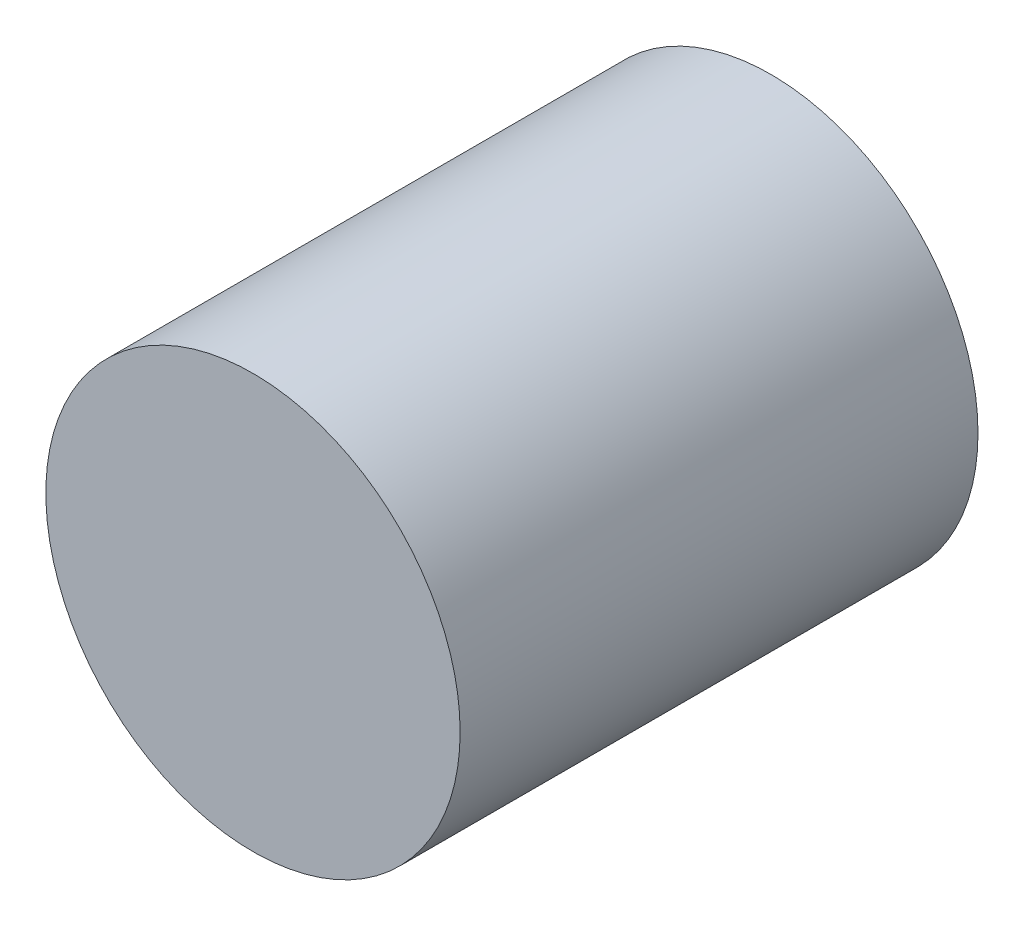
SolidWorks part; units mm, degrees
ref_plane "Front Plane" through (0, 0, 0) normal (0, 0, 1) x (1, 0, 0)
ref_plane "Top Plane" through (0, 0, 0) normal (0, 1, 0) x (1, 0, 0)
ref_plane "Right Plane" through (0, 0, 0) normal (1, 0, 0) x (0, 0, -1)
sketch "Sketch1" plane through (0, 0, 0) normal (0, 0, 1) x (1, 0, 0)
  circle A0 centre (0, 0) radius 50
  dimension "D1" = 100
extrude "Boss-Extrude1" add sketch "Sketch1" against normal blind 125
sketch "Sketch2" plane through (0, 0, 0) normal (1, 0, 0) x (0, 0, -1)
  line L0 (125, 0) -> (5.999, 0)
  line L1 (125, -50) -> (125, 50) construction
  line L2 (125, 0) -> (125, 45.8924)
  spline S0 degree 3 poles (5.999, 0) (42.885, 49.2992) (73.9435, 41.9695) (125, 45.8924) knots 0 0 0 0 1 1 1 1
revolve "Cut-Revolve1" cut sketch "Sketch2" angle 360 about L0
